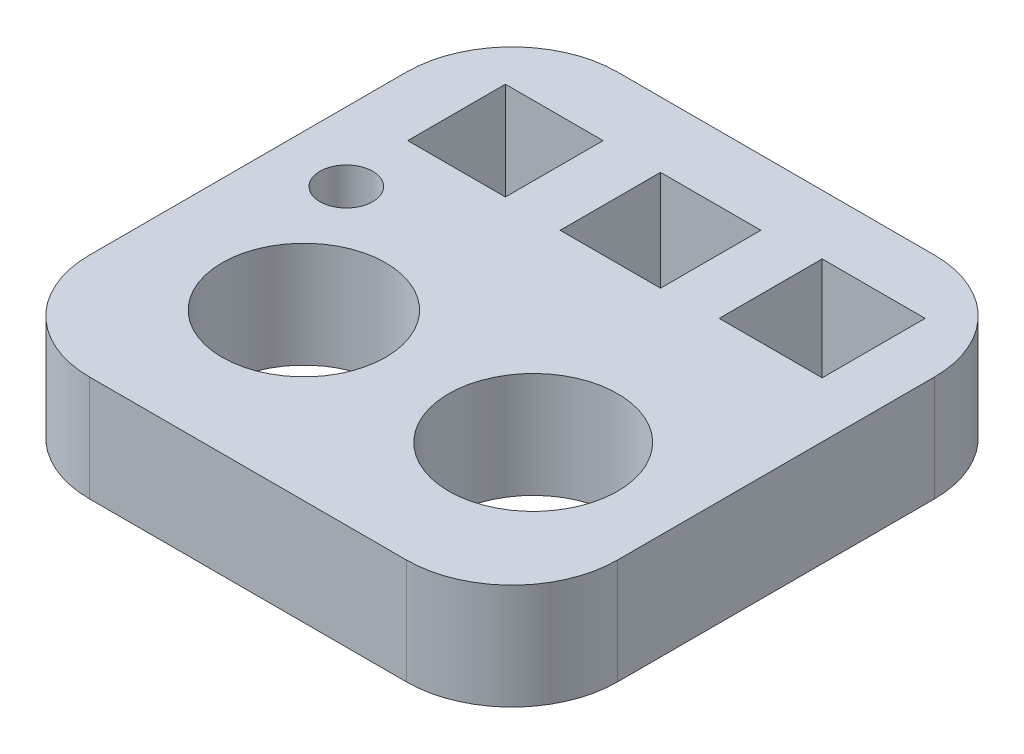
SolidWorks part; units mm, degrees
ref_plane "Front Plane" through (0, 0, 0) normal (0, 0, 1) x (1, 0, 0)
ref_plane "Top Plane" through (0, 0, 0) normal (0, 1, 0) x (1, 0, 0)
ref_plane "Right Plane" through (0, 0, 0) normal (1, 0, 0) x (0, 0, -1)
sketch "Sketch1" plane through (0, 0, 0) normal (0, 1, 0) x (1, 0, 0)
  line L1 (-51.0167, -33.2925) -> (-41.0167, -33.2925)
  line L2 (-51.0167, -33.2925) -> (-51.0167, -43.2925)
  line L3 (-51.0167, -43.2925) -> (-41.0167, -43.2925)
  line L4 (-41.0167, -33.2925) -> (-41.0167, -43.2925)
extrude "Boss-Extrude1" add sketch "Sketch1" along normal blind 2
sketch "Sketch2" plane through (0, 2, 0) normal (0, 1, 0) x (1, 0, 0)
  line L0 (-49.8808, -34.5532) -> (-48.0308, -34.5532)
  line L1 (-44.0162, -34.419) -> (-42.0662, -34.419)
  line L2 (-44.0162, -34.419) -> (-44.0162, -36.369)
  line L3 (-44.0162, -36.369) -> (-42.0662, -36.369)
  line L4 (-42.0662, -34.419) -> (-42.0662, -36.369)
  line L5 (-49.8808, -34.5532) -> (-49.8808, -36.4032)
  line L6 (-49.8808, -36.4032) -> (-48.0308, -36.4032)
  line L7 (-48.0308, -34.5532) -> (-48.0308, -36.4032)
  line L8 (-46.9667, -34.5299) -> (-45.0667, -34.5299)
  line L9 (-46.9667, -34.5299) -> (-46.9667, -36.4299)
  line L10 (-46.9667, -36.4299) -> (-45.0667, -36.4299)
  line L11 (-45.0667, -34.5299) -> (-45.0667, -36.4299)
  circle A0 centre (-48.0855, -40.1648) radius 1.55
  circle A1 centre (-43.7426, -40.1648) radius 1.6
  circle A2 centre (-49.7098, -37.7368) radius 0.5
extrude "Cut-Extrude1" cut sketch "Sketch2" against normal blind 10
fillet "Fillet1" radius 2 4 edges at (-51.0167, 1, 33.2925) (-51.0167, 1, 43.2925) (-41.0167, 1, 33.2925) (-41.0167, 1, 43.2925)
